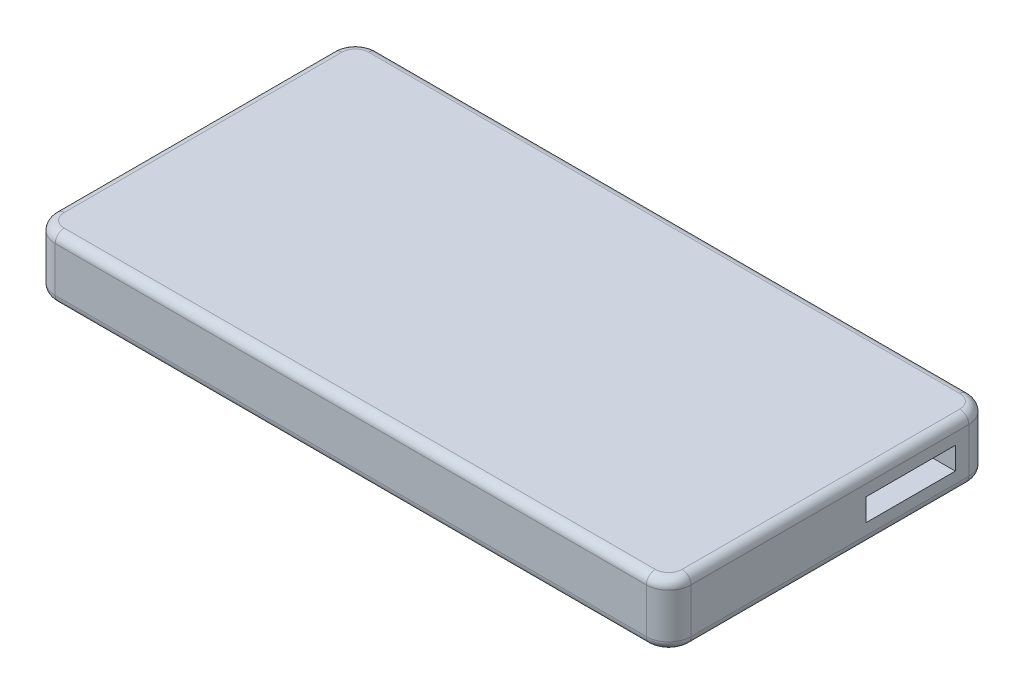
SolidWorks part; units mm, degrees
ref_plane "Front Plane" through (0, 0, 0) normal (0, 0, 1) x (1, 0, 0)
ref_plane "Top Plane" through (0, 0, 0) normal (0, 1, 0) x (1, 0, 0)
ref_plane "Right Plane" through (0, 0, 0) normal (1, 0, 0) x (0, 0, -1)
sketch "Sketch1" plane through (0, -5, 0) normal (0, 1, 0) x (1, 0, 0)
  line L1 (-111.4517, 33.7776) -> (20.5483, 33.7776)
  line L2 (-116.4517, 38.7776) -> (-116.4517, 100.7776)
  line L3 (-111.4517, 105.7776) -> (20.5483, 105.7776)
  line L4 (25.5483, 38.7776) -> (25.5483, 100.7776)
  arc A0 (-116.4517, 100.7776) -> (-111.4517, 105.7776) centre (-111.4517, 100.7776) cw
  arc A1 (-111.4517, 33.7776) -> (-116.4517, 38.7776) centre (-111.4517, 38.7776) cw
  arc A2 (20.5483, 33.7776) -> (25.5483, 38.7776) centre (20.5483, 38.7776) ccw
  arc A3 (20.5483, 105.7776) -> (25.5483, 100.7776) centre (20.5483, 100.7776) cw
  point P6 (-116.4517, 105.7776)
  point P11 (25.5483, 33.7776)
  point P14 (25.5483, 105.7776)
  dimension "D3" = 5
  dimension "D1" = 72
  dimension "D2" = 142
extrude "Boss-Extrude1" add sketch "Sketch1" along normal blind 14
fillet "Fillet1" radius 2 16 edges at (-114.9872, -5, -35.2421) (-116.4517, -5, -69.7776) (-114.9872, -5, -104.3131) (-45.4517, -5, -105.7776) (24.0839, -5, -104.3131) (25.5483, -5, -69.7776) (24.0839, -5, -35.2421) (-114.9872, 9, -35.2421) (-116.4517, 9, -69.7776) (-114.9872, 9, -104.3131) (-45.4517, 9, -105.7776) (24.0839, 9, -104.3131) (25.5483, 9, -69.7776) (24.0839, 9, -35.2421) (-45.4517, -5, -33.7776) (-45.4517, 9, -33.7776)
sketch "Sketch2" plane through (25.5483, 0, 0) normal (1, 0, 0) x (0, 0, -1)
  line L0 (105.7776, 2) -> (33.7776, 2) construction
  line L1 (105.7776, 7) -> (105.7776, -3) construction
  line L2 (33.7776, 7) -> (33.7776, -3) construction
  line L4 (97.7776, -0.5) -> (77.7776, -0.5)
  line L5 (97.7776, -0.5) -> (97.7776, 4.5)
  line L6 (97.7776, 4.5) -> (77.7776, 4.5)
  line L7 (77.7776, -0.5) -> (77.7776, 4.5)
  dimension "D1" = 2.5
  dimension "D2" = 5
  dimension "D3" = 20
  dimension "D4" = 8
extrude "Cut-Extrude1" cut sketch "Sketch2" against normal blind 20
